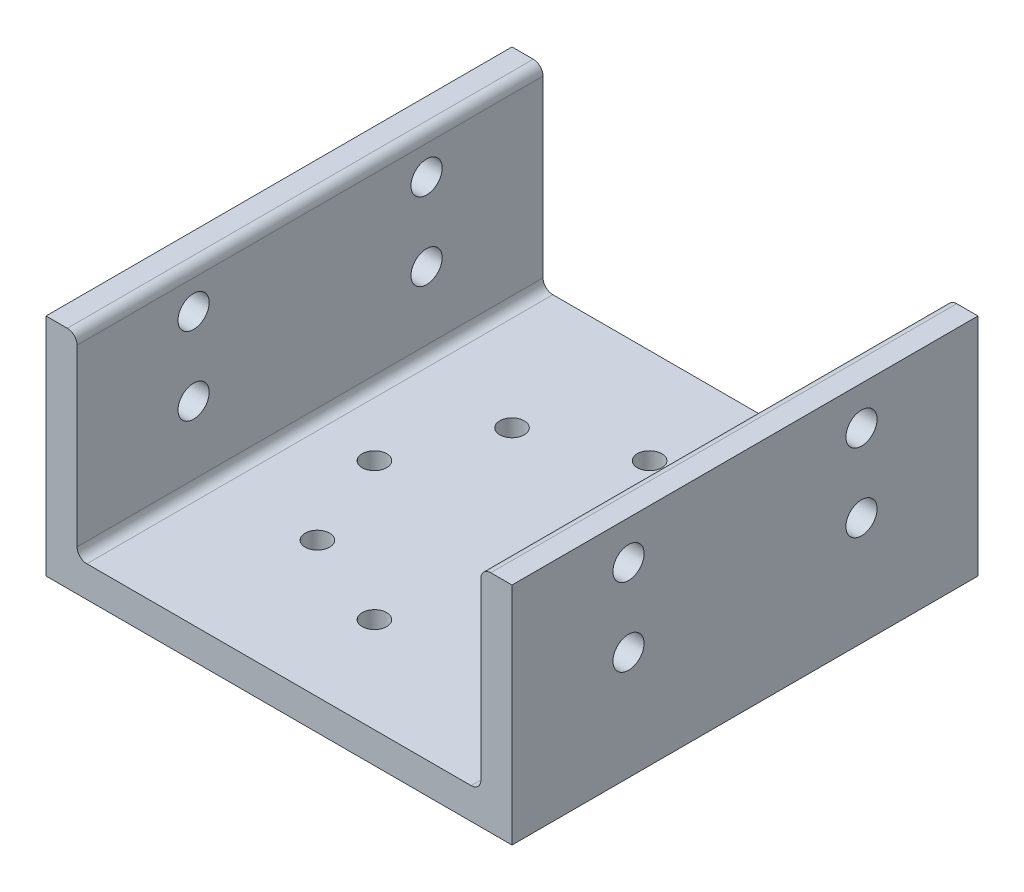
SolidWorks part; units mm, degrees
material "6061-T6 (SS)"
ref_plane "Front Plane" through (0, 0, 0) normal (0, 0, 1) x (1, 0, 0)
ref_plane "Top Plane" through (0, 0, 0) normal (0, 1, 0) x (1, 0, 0)
ref_plane "Right Plane" through (0, 0, 0) normal (1, 0, 0) x (0, 0, -1)
sketch "Sketch1" plane through (0, 0, 0) normal (0, 0, 1) x (1, 0, 0)
  line L1 (-38.1, 0) -> (38.1, 0)
  line L2 (-38.1, 0) -> (-38.1, 4.3894)
  line L3 (-33.02, 5.08) -> (33.02, 5.08)
  line L4 (38.1, 0) -> (38.1, 3.175)
  line L6 (-38.1, 4.3894) -> (-38.1, 36.83)
  line L7 (-38.1, 36.83) -> (-33.02, 36.83)
  line L8 (-33.02, 5.08) -> (-33.02, 36.83)
  line L10 (38.1, 3.175) -> (38.1, 36.83)
  line L11 (38.1, 36.83) -> (33.02, 36.83)
  line L12 (33.02, 5.08) -> (33.02, 36.83)
  point P10 (0, 0)
  dimension "D1" = 76.2
  dimension "D2" = 31.75
  dimension "D3" = 5.08
  dimension "D4" = 5.08
  dimension "D5" = 5.08
extrude "Boss-Extrude1" add sketch "Sketch1" along normal blind 76.2
fillet "Fillet1" radius 1.6 4 edges at (33.02, 36.83, 38.1) (33.02, 5.08, 38.1) (-33.02, 36.83, 38.1) (-33.02, 5.08, 38.1)
sketch "Sketch2" plane through (0, 0, 0) normal (0, -1, 0) x (1, 0, 0)
  line L0 (0, 76.2) -> (0, 0) construction
  line L1 (-38.1, 76.2) -> (38.1, 76.2) construction
  circle A0 centre (0, 38.1) radius 22.5 construction
  circle A1 centre (0, 60.6) radius 2
  circle A2 centre (15.9099, 54.0099) radius 2
  circle A3 centre (22.5, 38.1) radius 2
  circle A4 centre (15.9099, 22.1901) radius 2
  circle A5 centre (0, 15.6) radius 2
  circle A6 centre (-15.9099, 22.1901) radius 2
  circle A7 centre (-22.5, 38.1) radius 2
  circle A8 centre (-15.9099, 54.0099) radius 2
  point P25 (0, 38.1)
  dimension "D1" = 45
  dimension "D2" = 4
  dimension "D3" = 8
extrude "Cut-Extrude2" cut sketch "Sketch2" against normal through all
sketch "Sketch3" plane through (-38.1, 0, 0) normal (-1, 0, 0) x (0, 0, 1)
  line L0 (0, 17.78) -> (38.1, 17.78) construction
  line L1 (0, 36.83) -> (0, 35.23) construction
  line L2 (0, 36.83) -> (0, 0) construction
  line L3 (76.2, 36.83) -> (0, 36.83) construction
  line L4 (0, 24.13) -> (0, 36.83) construction
  line L5 (0, 24.13) -> (0, 11.43) construction
  line L6 (76.2, 36.83) -> (76.2, 0) construction
  line L7 (38.1, 30.48) -> (0, 30.48) construction
  line L8 (76.2, 17.78) -> (38.1, 17.78) construction
  line L9 (76.2, 30.48) -> (38.1, 30.48) construction
  circle A0 centre (19.05, 30.48) radius 2.55
  circle A1 centre (19.05, 17.78) radius 2.55
  circle A2 centre (57.15, 17.78) radius 2.55
  circle A3 centre (57.15, 30.48) radius 2.55
  dimension "D2" = 5.1
  dimension "D1" = 25.4
extrude "Cut-Extrude3" cut sketch "Sketch3" against normal through all
